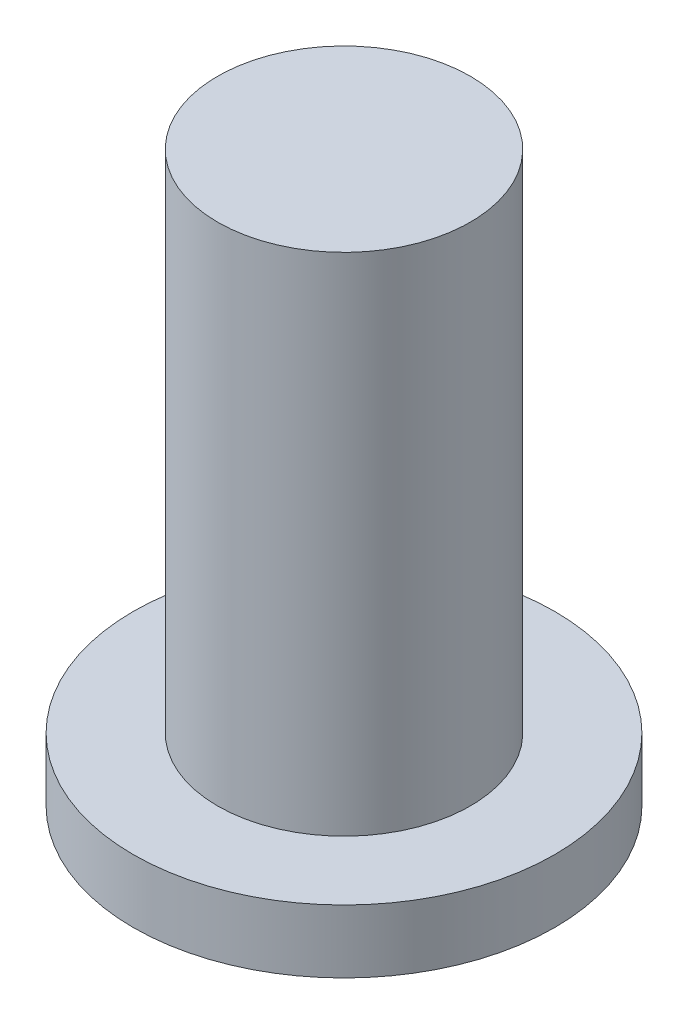
SolidWorks part; units mm, degrees
ref_plane "Front Plane" through (0, 0, 0) normal (0, 0, 1) x (1, 0, 0)
ref_plane "Top Plane" through (0, 0, 0) normal (0, 1, 0) x (1, 0, 0)
ref_plane "Right Plane" through (0, 0, 0) normal (1, 0, 0) x (0, 0, -1)
sketch "Sketch2" plane through (0, 0, 0) normal (0, 1, 0) x (1, 0, 0)
  circle A0 centre (0, 0) radius 5
extrude "Boss-Extrude1" add sketch "Sketch2" along normal blind 1.5
sketch "Sketch3" plane through (0, 1.5, 0) normal (0, 1, 0) x (1, 0, 0)
  circle A0 centre (0, 0) radius 3
extrude "Boss-Extrude2" add sketch "Sketch3" along normal blind 12
